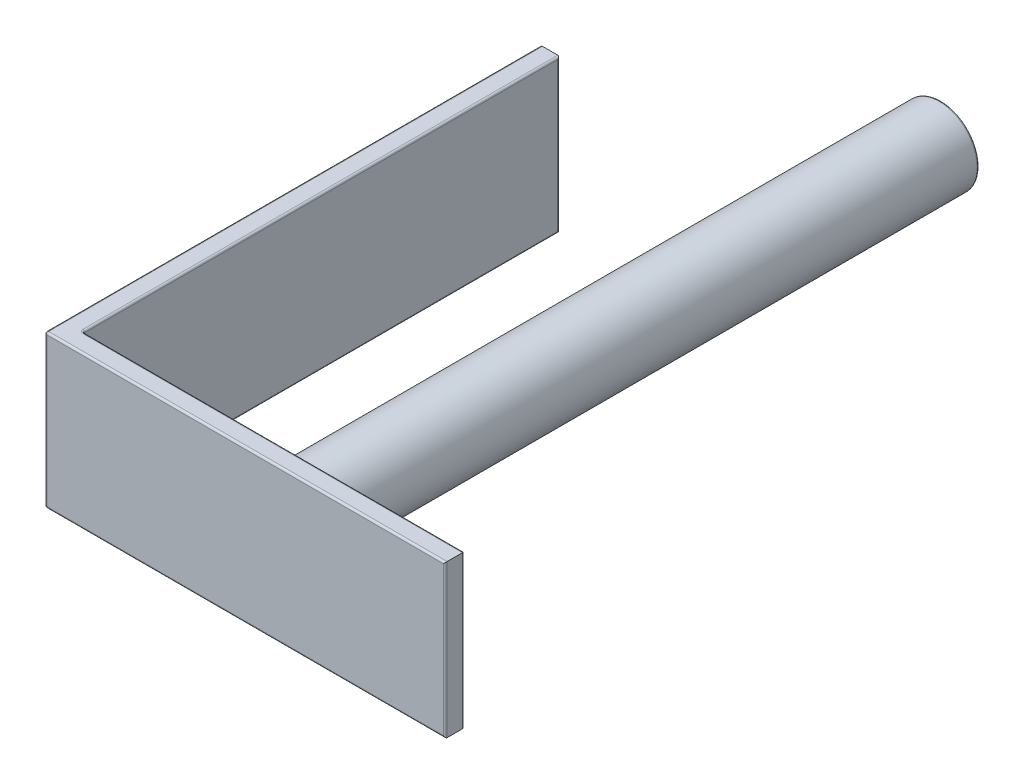
SolidWorks part; units mm, degrees
ref_plane "Front Plane" through (0, 0, 0) normal (0, 0, 1) x (1, 0, 0)
ref_plane "Top Plane" through (0, 0, 0) normal (0, 1, 0) x (1, 0, 0)
ref_plane "Right Plane" through (0, 0, 0) normal (1, 0, 0) x (0, 0, -1)
sketch "Sketch1" plane through (0, 0, 0) normal (0, 0, 1) x (1, 0, 0)
  circle A0 centre (0, 0) radius 50.8
  dimension "D1" = 101.6
extrude "Boss-Extrude1" add sketch "Sketch1" against normal blind 889
sketch "Sketch3" plane through (0, 0, 0) normal (0, 1, 0) x (1, 0, 0)
  line L0 (254, 0) -> (-254, 0)
  line L1 (-254, 0) -> (-254, 635)
  point P3 (0, 0)
  dimension "D1" = 508
  dimension "D2" = 635
extrude "Extrude-Thin1" add sketch "Sketch3" along normal mid plane 203.2 thin thin type one direction reverse wall 25.4
fillet "Fillet1" radius 2.54 16 edges at (0, -101.6, 0) (-279.4, 0, 25.4) (-12.7, 101.6, 25.4) (254, 0, 25.4) (-12.7, -101.6, 25.4) (50.8, 0, 0) (50.8, 0, -889) (-254, 0, 0) (-279.4, 0, -635) (-254, 0, -635) (254, 0, 0) (-254, -101.6, -317.5) (-279.4, 101.6, -304.8) (-279.4, -101.6, -304.8) (-254, 101.6, -317.5) (0, 101.6, 0)
